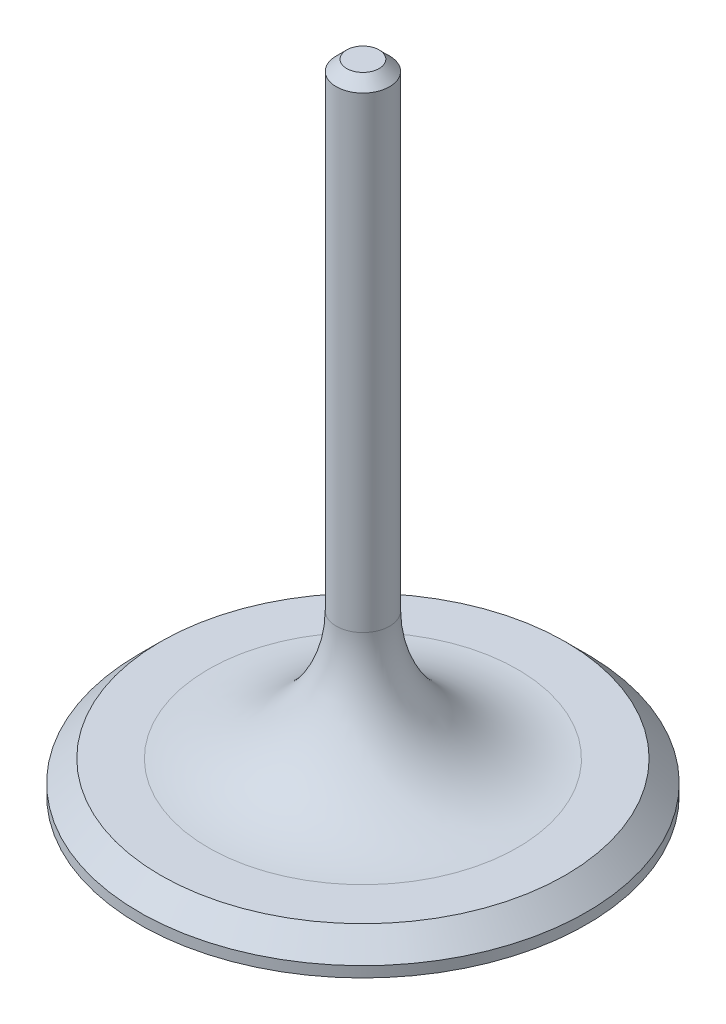
SolidWorks part; units mm, degrees
ref_plane "Front Plane" through (0, 0, 0) normal (0, 0, 1) x (1, 0, 0)
ref_plane "Top Plane" through (0, 0, 0) normal (0, 1, 0) x (1, 0, 0)
ref_plane "Right Plane" through (0, 0, 0) normal (1, 0, 0) x (0, 0, -1)
sketch "Sketch1" plane through (0, 0, 0) normal (0, 0, 1) x (1, 0, 0)
  line L0 (0, 0) -> (50000, 0) construction
  line L1 (24.13, 3.81) -> (26.67, 1.27)
  line L2 (3.18, 76.02) -> (3.18, 19.06)
  line L3 (18.43, 3.81) -> (24.13, 3.81)
  line L4 (26.67, 1.27) -> (26.67, 0)
  line L5 (26.67, 0) -> (0, 0)
  line L6 (3.18, 76.02) -> (0, 76.02)
  line L7 (0, 0) -> (0, -50000) construction
  line L8 (0, 76.02) -> (0, 0)
  arc A0 (3.18, 19.06) -> (18.43, 3.81) centre (18.43, 19.06) ccw
  dimension "D3" = 15.25
  dimension "D7" = 45
  dimension "D1" = 1.27
  dimension "D2" = 76.02
  dimension "D4" = 3.81
  dimension "D5" = 6.36
  dimension "D6" = 53.34
revolve "Revolve1" add sketch "Sketch1" angle 360 about L8
chamfer "Chamfer1" distance 1.25 angle 45 1 edges at (-3.18, 76.02, 0)
